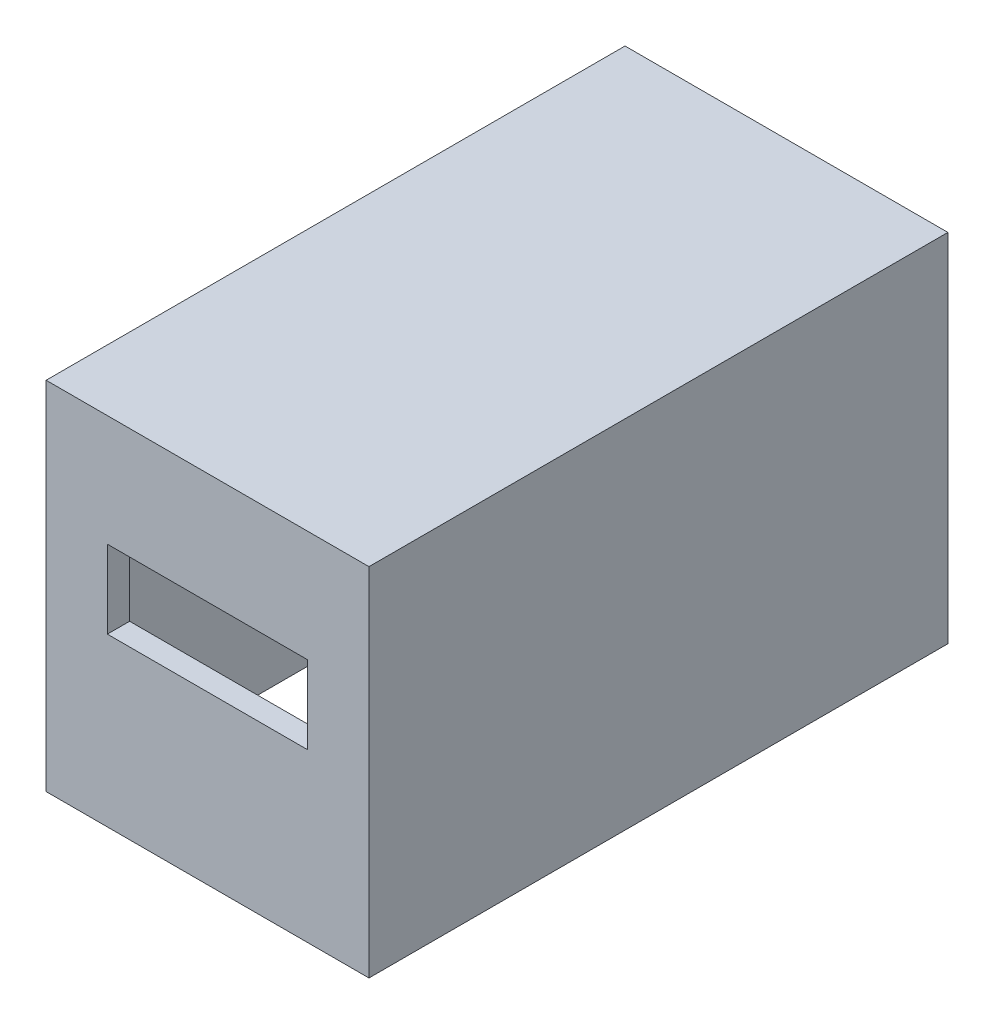
SolidWorks part; units mm, degrees
ref_plane "Ön Düzlem" through (0, 0, 0) normal (0, 0, 1) x (1, 0, 0)
ref_plane "Üst Düzlem" through (0, 0, 0) normal (0, 1, 0) x (1, 0, 0)
ref_plane "Sağ Düzlem" through (0, 0, 0) normal (1, 0, 0) x (0, 0, -1)
sketch "Çizim1" plane through (0, 0, 0) normal (0, 1, 0) x (1, 0, 0)
  line L0 (-7.25, 13) -> (7.25, 13)
  line L1 (-6.25, -12) -> (6.25, -12)
  line L2 (-6.25, -12) -> (-6.25, 12)
  line L3 (-6.25, 12) -> (6.25, 12)
  line L4 (6.25, -12) -> (6.25, 12)
  line L5 (-6.25, -12) -> (6.25, 12) construction
  line L6 (-6.25, 12) -> (6.25, -12) construction
  line L7 (7.25, -13) -> (7.25, 13)
  line L8 (-7.25, -13) -> (7.25, -13)
  line L9 (-7.25, -13) -> (-7.25, 13)
  point P0 (0, 0)
  dimension "D1" = 24
  dimension "D2" = 12.5
  dimension "D3" = 1
extrude "Yükseklik-Ekstrüzyon1" add sketch "Çizim1" along normal blind 15
sketch "Çizim2" plane through (0, 15, 0) normal (0, 1, 0) x (1, 0, 0)
  line L0 (-7.25, -13) -> (7.25, -13) construction
  line L1 (7.25, -13) -> (7.25, 13) construction
  line L2 (7.25, 13) -> (-7.25, 13) construction
  line L3 (-7.25, 13) -> (-7.25, -13) construction
  line L4 (-7.25, -13) -> (7.25, -13)
  line L5 (7.25, -13) -> (7.25, 13)
  line L6 (7.25, 13) -> (-7.25, 13)
  line L7 (-7.25, 13) -> (-7.25, -13)
extrude "Yükseklik-Ekstrüzyon2" add sketch "Çizim2" along normal blind 1
sketch "Çizim3" plane through (0, 0, 13) normal (0, 0, 1) x (1, 0, 0)
  line L0 (0, 16) -> (0, 11)
  line L1 (-7.25, 16) -> (7.25, 16) construction
  line L2 (0, 11) -> (-4.5, 11)
  line L4 (-4.5, 11) -> (4.5, 11)
  line L5 (-4.5, 11) -> (-4.5, 7.5)
  line L6 (-4.5, 7.5) -> (4.5, 7.5)
  line L7 (4.5, 11) -> (4.5, 7.5)
  dimension "D1" = 5
  dimension "D2" = 4.5
  dimension "D3" = 3.5
  dimension "D4" = 9
extrude "Kes-Ekstrüzyon1" cut sketch "Çizim3" against normal blind 2 contours L7 L4 L2 L5 L6
